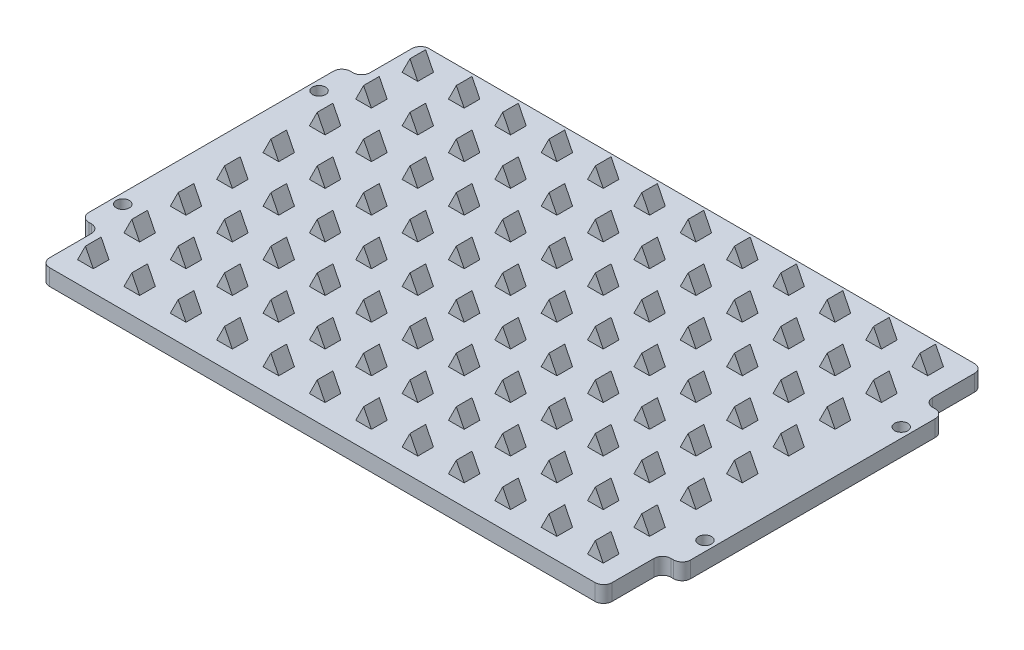
SolidWorks part; units mm, degrees
ref_plane "Front Plane" through (0, 0, 0) normal (0, 0, 1) x (1, 0, 0)
ref_plane "Top Plane" through (0, 0, 0) normal (0, 1, 0) x (1, 0, 0)
ref_plane "Right Plane" through (0, 0, 0) normal (1, 0, 0) x (0, 0, -1)
sketch "Sketch1" plane through (0, 0, 0) normal (0, 1, 0) x (1, 0, 0)
  line L1 (-54.61, -36.83) -> (54.61, -36.83)
  line L2 (-54.61, -36.83) -> (-54.61, 36.83)
  line L3 (-54.61, 36.83) -> (54.61, 36.83)
  line L4 (54.61, -36.83) -> (54.61, 36.83)
  line L5 (-54.61, -36.83) -> (54.61, 36.83) construction
  line L6 (-54.61, 36.83) -> (54.61, -36.83) construction
  point P0 (0, 0)
  dimension "D1" = 109.22
  dimension "D2" = 73.66
extrude "Boss-Extrude1" add sketch "Sketch1" against normal blind 3.175
ref_plane "Plane1" through (0, 0, -31.75) normal (0, 0, 1) x (1, 0, 0)
sketch "Sketch2" plane through (0, 0, -31.75) normal (0, 0, 1) x (1, 0, 0)
  line L0 (-51.562, 0) -> (-50.038, 3.048)
  line L3 (-50.038, 0) -> (-51.562, 0)
  line L4 (-50.038, 3.048) -> (-50.038, 0) construction
  line L5 (-50.038, 3.048) -> (-48.514, 0)
  line L6 (-54.61, 0) -> (54.61, 0) construction
  line L7 (-48.514, 0) -> (-50.038, 0)
  point P5 (-50.8, 0)
  dimension "D1" = 1.524
  dimension "D2" = 3.048
  dimension "D3" = 50.8
extrude "Boss-Extrude3" add sketch "Sketch2" along normal mid plane 3.048
pattern_linear "LPattern1" count 12 spacing 9 along (1, 0, 0) count 8 spacing 9 along (0, 0, 1) of "Boss-Extrude3"
sketch "Sketch3" plane through (0, 0, 0) normal (0, 1, 0) x (1, 0, 0)
  line L0 (-54.61, 36.83) -> (-54.61, -36.83) construction
  line L1 (-54.61, 25.4) -> (-58.42, 25.4)
  line L2 (-54.61, 25.4) -> (-54.61, -25.4)
  line L3 (-54.61, -25.4) -> (-58.42, -25.4)
  line L4 (-58.42, 25.4) -> (-58.42, -25.4)
  line L5 (0, 0) -> (0, 36.83) construction
  line L6 (54.61, 36.83) -> (-54.61, 36.83) construction
  line L7 (58.42, 25.4) -> (58.42, -25.4)
  line L8 (54.61, -25.4) -> (58.42, -25.4)
  line L9 (54.61, 25.4) -> (54.61, -25.4)
  line L10 (54.61, 25.4) -> (58.42, 25.4)
  circle A0 centre (-56.515, 19.05) radius 1.27
  circle A1 centre (-56.515, -19.05) radius 1.27
  circle A2 centre (56.515, -19.05) radius 1.27
  circle A3 centre (56.515, 19.05) radius 1.27
  point P6 (-58.42, 0)
  point P11 (-56.515, 25.4)
  dimension "D3" = 2.54
  dimension "D1" = 3.81
  dimension "D2" = 50.8
  dimension "D4" = 19.05
  dimension "D5" = 2
extrude "Boss-Extrude2" add sketch "Sketch3" against normal blind 3.175
fillet "Fillet1" radius 1.651 12 edges at (54.61, -1.5875, -36.83) (54.61, -1.5875, -25.4) (58.42, -1.5875, -25.4) (58.42, -1.5875, 25.4) (54.61, -1.5875, 25.4) (54.61, -1.5875, 36.83) (-54.61, -1.5875, 36.83) (-54.61, -1.5875, 25.4) (-58.42, -1.5875, 25.4) (-58.42, -1.5875, -25.4) (-54.61, -1.5875, -25.4) (-54.61, -1.5875, -36.83)
